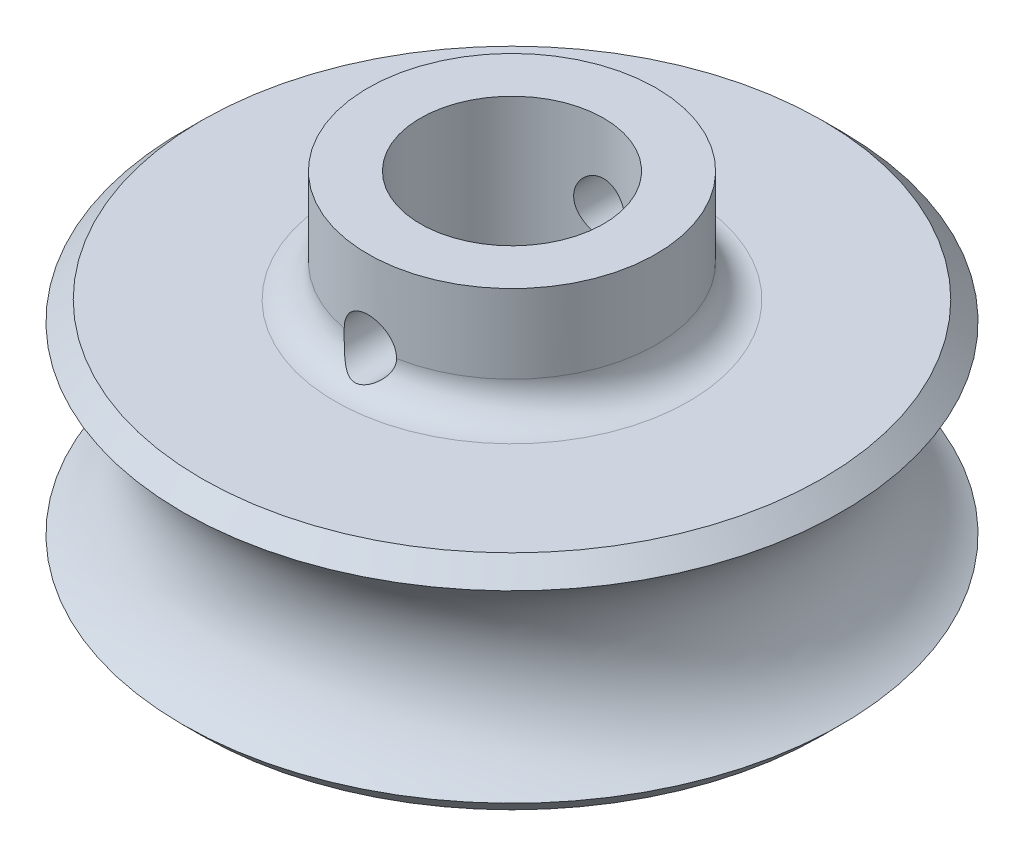
SolidWorks part; units mm, degrees
ref_plane "Plan de face" through (0, 0, 0) normal (0, 0, 1) x (1, 0, 0)
ref_plane "Plan de dessus" through (0, 0, 0) normal (0, 1, 0) x (1, 0, 0)
ref_plane "Plan de droite" through (0, 0, 0) normal (1, 0, 0) x (0, 0, -1)
sketch "Sketch1" plane through (0, 0, 0) normal (0, 0, 1) x (1, 0, 0)
  line L0 (3.5, 8.5) -> (3.5, 0)
  line L2 (0, 0) -> (0, 8.5) construction
  line L4 (3.5, 0) -> (11.85, 0)
  line L5 (6.75, 8.5) -> (11.85, 8.5)
  line L6 (11.85, 0) -> (12.5871, 0.7371)
  line L7 (11.85, 8.5) -> (12.5871, 7.7629)
  line L8 (0, 0) -> (3.5, 0) construction
  line L9 (0, 4.25) -> (14.5, 4.25) construction
  line L10 (5.5, 9.75) -> (5.5, 12.75)
  line L11 (3.5, 8.5) -> (3.5, 12.75)
  line L12 (3.5, 12.75) -> (5.5, 12.75)
  line L13 (6.75, 8.5) -> (3.5, 8.5) construction
  arc A2 (12.5871, 7.7629) -> (12.5871, 0.7371) centre (14.5, 4.25) ccw
  arc A3 (6.75, 8.5) -> (5.5, 9.75) centre (6.75, 9.75) cw
  dimension "D3" = 8
  dimension "D9" = 4.25
  dimension "D8" = 1.25
  dimension "D1" = 8.5
  dimension "D2" = 8.35
  dimension "D4" = 3.5
  dimension "D5" = 14.5
  dimension "D6" = 1.0424
  dimension "D7" = 1.0424
  dimension "D10" = 6.35
  dimension "D11" = 2
revolve "Revolve1" add sketch "Sketch1" angle 360 about L2
sketch "Sketch2" plane through (0, 0, 0) normal (0, 0, 1) x (1, 0, 0)
  line L1 (0, 9.75) -> (0, 12.75) construction
  line L2 (3.5, 12.75) -> (-3.5, 12.75) construction
  circle A0 centre (0, 9.75) radius 1
  dimension "D2" = 2
  dimension "D1" = 3
extrude "Cut-Extrude1" cut sketch "Sketch2" against normal up to next and the other way up to next
